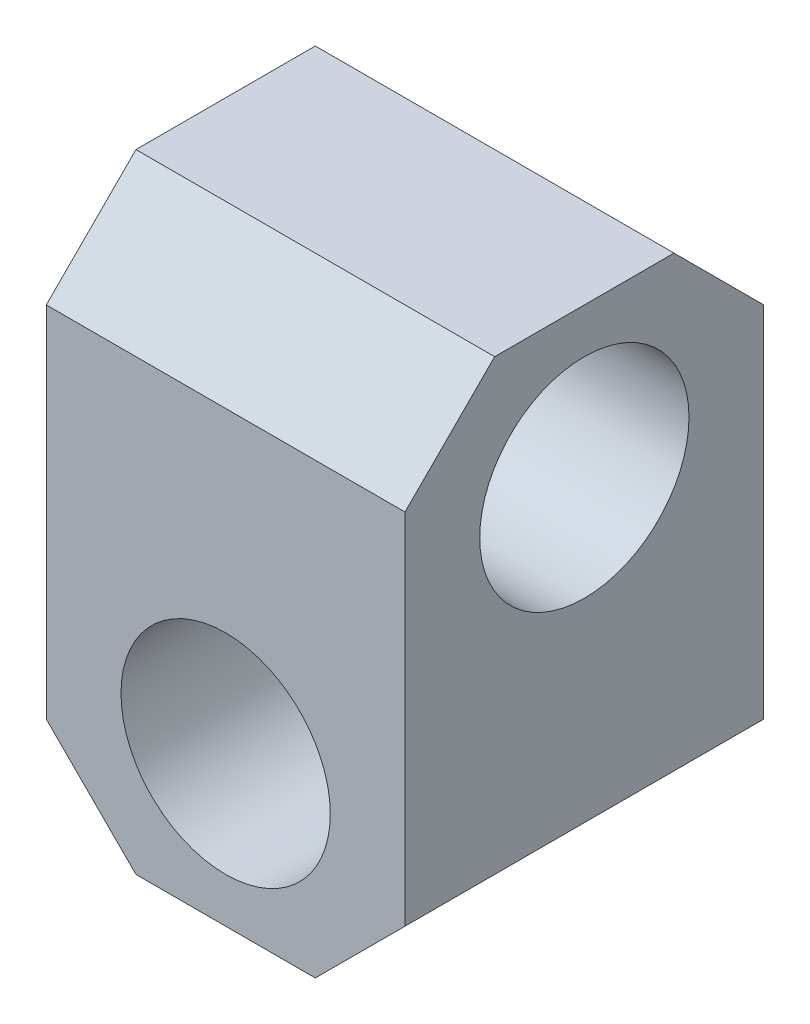
SolidWorks part; units mm, degrees
material "PLA"
ref_plane "Front Plane" through (0, 0, 0) normal (0, 0, 1) x (1, 0, 0)
ref_plane "Top Plane" through (0, 0, 0) normal (0, 1, 0) x (1, 0, 0)
ref_plane "Right Plane" through (0, 0, 0) normal (1, 0, 0) x (0, 0, -1)
sketch "Sketch1" plane through (0, 0, 0) normal (0, 1, 0) x (1, 0, 0)
  line L1 (-3, -3) -> (3, -3)
  line L2 (-3, -3) -> (-3, 3)
  line L3 (-3, 3) -> (3, 3)
  line L4 (3, -3) -> (3, 3)
  line L5 (-3, -3) -> (3, 3) construction
  line L6 (-3, 3) -> (3, -3) construction
  point P0 (0, 0)
  dimension "D1" = 6
  dimension "D2" = 6
extrude "Boss-Extrude1" add sketch "Sketch1" along normal mid plane 9
sketch "Sketch2" plane through (0, 0, 0) normal (0, 0, 1) x (1, 0, 0)
  line L0 (0, -1000) -> (0, 49000) construction
  line L1 (-3, -4.5) -> (3, -4.5) construction
  circle A0 centre (0, -2) radius 1.75
  dimension "D1" = 3.5
  dimension "D2" = 2.5
extrude "Cut-Extrude1" cut sketch "Sketch2" against normal through all both and the other way through all
sketch "Sketch3" plane through (-3, 0, 0) normal (-1, 0, 0) x (0, 0, 1)
  line L0 (0, -1000) -> (0, 49000) construction
  line L1 (-3, 4.5) -> (3, 4.5) construction
  circle A0 centre (0, 2) radius 1.75
  dimension "D1" = 3.5
  dimension "D2" = 2.5
extrude "Cut-Extrude2" cut sketch "Sketch3" against normal through all
chamfer "Chamfer1" distance 1.5 angle 45 4 edges at (0, 4.5, -3) (0, 4.5, 3) (3, -4.5, 0) (-3, -4.5, 0)
